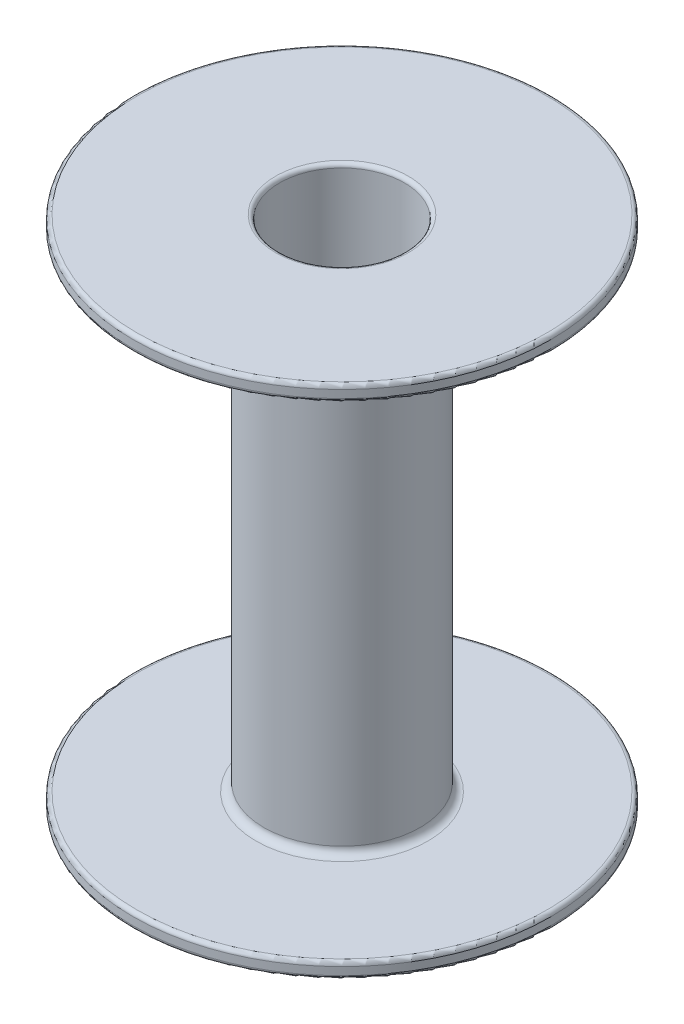
SolidWorks part; units mm, degrees
ref_plane "Alzado" through (0, 0, 0) normal (0, 0, 1) x (1, 0, 0)
ref_plane "Planta" through (0, 0, 0) normal (0, 1, 0) x (1, 0, 0)
ref_plane "Vista lateral" through (0, 0, 0) normal (1, 0, 0) x (0, 0, -1)
sketch "Croquis1" plane through (0, 0, 0) normal (0, 0, 1) x (1, 0, 0)
  line L0 (0, 20.9742) -> (0, -28.156) construction
  line L1 (8, 37.344) -> (8, -27.656)
  line L2 (8.5, 37.844) -> (26.26, 37.844)
  line L3 (26.76, 37.344) -> (26.76, 36.344)
  line L4 (26.26, 35.844) -> (10.5, 35.844)
  line L5 (0, 4.844) -> (21.7843, 4.844) construction
  line L7 (26.76, -27.656) -> (26.76, -26.656)
  line L8 (26.26, -26.156) -> (11, -26.156)
  line L9 (10, 35.344) -> (10, -25.156)
  line L10 (8.5, -28.156) -> (26.26, -28.156)
  arc A2 (10, -25.156) -> (11, -26.156) centre (11, -25.156) ccw
  arc A3 (8.5, -28.156) -> (8, -27.656) centre (8.5, -27.656) cw
  arc A4 (8.5, 37.844) -> (8, 37.344) centre (8.5, 37.344) ccw
  arc A5 (26.76, 37.344) -> (26.26, 37.844) centre (26.26, 37.344) ccw
  arc A6 (26.26, 35.844) -> (26.76, 36.344) centre (26.26, 36.344) ccw
  arc A7 (10, 35.344) -> (10.5, 35.844) centre (10.5, 35.344) cw
  arc A8 (26.26, -26.156) -> (26.76, -26.656) centre (26.26, -26.656) cw
  arc A9 (26.76, -27.656) -> (26.26, -28.156) centre (26.26, -27.656) cw
  point P15 (26.76, -28.156)
  point P18 (26.76, -26.156)
  point P21 (10, -26.156)
  point P24 (8, -28.156)
  point P27 (8, 37.844)
  point P30 (26.76, 37.844)
  point P33 (26.76, 35.844)
  point P36 (10, 35.844)
  dimension "D7" = 1
  dimension "D1" = 8
  dimension "D2" = 66
  dimension "D3" = 18.76
  dimension "D4" = 2
  dimension "D6" = 2
revolve "Revolución1" add sketch "Croquis1" angle 360 about L0
